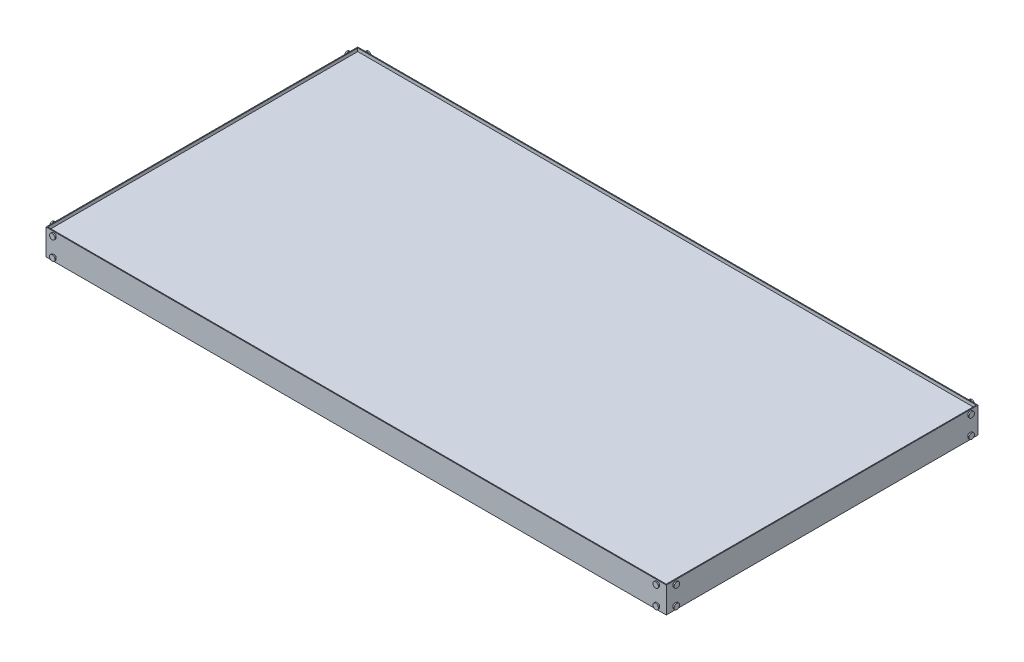
SolidWorks part; units mm, degrees
material "Plain Carbon Steel"
ref_plane "Front Plane" through (0, 0, 0) normal (0, 0, 1) x (1, 0, 0)
ref_plane "Top Plane" through (0, 0, 0) normal (0, 1, 0) x (1, 0, 0)
ref_plane "Right Plane" through (0, 0, 0) normal (1, 0, 0) x (0, 0, -1)
sketch "Sketch1" plane through (0, 0, 0) normal (0, 1, 0) x (1, 0, 0)
  line L1 (-612.775, -307.975) -> (612.775, -307.975)
  line L2 (-612.775, -307.975) -> (-612.775, 307.975)
  line L3 (-612.775, 307.975) -> (612.775, 307.975)
  line L4 (612.775, -307.975) -> (612.775, 307.975)
  line L5 (-612.775, -307.975) -> (612.775, 307.975) construction
  line L6 (-612.775, 307.975) -> (612.775, -307.975) construction
  point P0 (0, 0)
  dimension "D1" = 1225.55
  dimension "D2" = 615.95
ref_plane "Plane1" through (0, 5.08, 0) normal (0, 1, 0) x (1, 0, 0)
sketch "Sketch2" plane through (0, 5.08, 0) normal (0, 1, 0) x (1, 0, 0)
  line L0 (612.775, -307.975) -> (612.775, 307.975) construction
  line L1 (-612.775, 307.975) -> (612.775, 307.975)
  line L2 (-612.775, 307.975) -> (-612.775, -307.975)
  line L3 (-612.775, -307.975) -> (612.775, -307.975)
  line L4 (612.775, 307.975) -> (612.775, -307.975)
  line L5 (-612.775, 307.975) -> (612.775, 307.975) construction
  line L6 (-612.775, -307.975) -> (-612.775, 307.975) construction
  line L7 (-612.775, -307.975) -> (612.775, -307.975) construction
extrude "Boss-Extrude1" add sketch "Sketch2" against normal blind 51.308
sketch "Sketch3" plane through (0, 5.08, 0) normal (0, 1, 0) x (1, 0, 0)
  line L8 (-611.124, 306.324) -> (-611.124, -306.324)
  line L9 (-611.124, -306.324) -> (611.124, -306.324)
  line L10 (611.124, -306.324) -> (611.124, 306.324)
  line L11 (611.124, 306.324) -> (-611.124, 306.324)
  line L12 (-611.124, 306.324) -> (-611.124, -306.324)
  line L13 (-611.124, -306.324) -> (611.124, -306.324)
  line L14 (611.124, -306.324) -> (611.124, 306.324)
  line L15 (611.124, 306.324) -> (-611.124, 306.324)
  dimension "D1" = 1.651
extrude "Cut-Extrude1" cut sketch "Sketch3" against normal blind 13.1064
sketch "Sketch4" plane through (0, -8.0264, 0) normal (0, 1, 0) x (1, 0, 0)
  line L1 (-609.6, -304.8) -> (609.6, -304.8)
  line L2 (-609.6, -304.8) -> (-609.6, 304.8)
  line L3 (-609.6, 304.8) -> (609.6, 304.8)
  line L4 (609.6, -304.8) -> (609.6, 304.8)
  line L5 (-609.6, -304.8) -> (609.6, 304.8) construction
  line L6 (-609.6, 304.8) -> (609.6, -304.8) construction
  point P0 (0, 0)
  dimension "D1" = 1219.2
  dimension "D2" = 609.6
extrude "Boss-Extrude2" add sketch "Sketch4" along normal offset from surface (8.3312 mm away) 4.7752 separate body up to face at (0, 5.08, 0)
sketch "Sketch5" plane through (0, 0, 307.975) normal (0, 0, 1) x (1, 0, 0)
  line L0 (612.775, -46.228) -> (612.775, 5.08) construction
  line L1 (-612.775, 5.08) -> (612.775, 5.08) construction
  line L2 (596.0872, -0.9652) -> (596.0872, -37.5412) construction
  circle A0 centre (596.0872, -0.9652) radius 5.461 construction
  circle A1 centre (596.0872, -0.9652) radius 3.556
  circle A2 centre (596.0872, -37.5412) radius 3.556
  dimension "D2" = 10.922
  dimension "D4" = 7.112
  dimension "D1" = 11.2268
  dimension "D3" = 11.5062
  dimension "D5" = 36.576
extrude "Boss-Extrude3" add sketch "Sketch5" along normal blind 2.032
sketch "Sketch6" plane through (0, 0, 310.007) normal (0, 0, 1) x (1, 0, 0)
  circle A0 centre (596.0872, -0.9652) radius 5.461
  circle A1 centre (596.0872, -37.5412) radius 5.461
  circle A2 centre (596.0872, -37.5412) radius 3.556 construction
  circle A3 centre (596.0872, -0.9652) radius 3.556 construction
  circle A4 centre (596.0872, -0.9652) radius 5.461 construction
extrude "Boss-Extrude4" add sketch "Sketch6" along normal offset from surface (2.286 mm away) 4.318 up to face at (599.6432, -37.5412, 307.975) offset beyond the face yes
sketch "Sketch7" plane through (612.775, 0, 0) normal (1, 0, 0) x (0, 0, -1)
  line L0 (-291.2872, -0.9652) -> (-291.2872, -37.5412) construction
  line L1 (-307.975, -46.228) -> (-307.975, 5.08) construction
  line L2 (-307.975, 5.08) -> (307.975, 5.08) construction
  circle A0 centre (-291.2872, -0.9652) radius 5.461 construction
  circle A1 centre (-291.2872, -0.9652) radius 3.556
  circle A2 centre (-291.2872, -37.5412) radius 3.556
  dimension "D2" = 10.922
  dimension "D4" = 7.112
  dimension "D1" = 11.2268
  dimension "D3" = 11.5062
  dimension "D5" = 36.576
extrude "Boss-Extrude5" add sketch "Sketch7" along normal blind 2.032
sketch "Sketch8" plane through (614.807, 0, 0) normal (1, 0, 0) x (0, 0, -1)
  circle A0 centre (-291.2872, -0.9652) radius 5.461
  circle A1 centre (-291.2872, -37.5412) radius 5.461
  circle A2 centre (-291.2872, -37.5412) radius 3.556 construction
  circle A4 centre (-291.2872, -0.9652) radius 5.461 construction
extrude "Boss-Extrude6" add sketch "Sketch8" along normal offset from surface (2.286 mm away) 4.318 up to face at (612.775, -37.5412, 287.7312) offset beyond the face yes
mirror "Mirror2" about plane through (0, 0, 0) normal (0, 0, 1) of "Boss-Extrude6", "Boss-Extrude5", "Boss-Extrude4", "Boss-Extrude3"
mirror "Mirror3" about plane through (0, 0, 0) normal (1, 0, 0) of "Mirror2", "Boss-Extrude6", "Boss-Extrude5", "Boss-Extrude4", "Boss-Extrude3"
equation "\"D1@Sketch7\"=\"D1@Sketch5\""
equation "\"D2@Sketch7\"=\"D2@Sketch5\""
equation "\"D3@Sketch7\"=\"D3@Sketch5\""
equation "\"D4@Sketch7\"=\"D4@Sketch5\""
equation "\"D5@Sketch7\"=\"D5@Sketch5\""
equation "\"D1@Boss-Extrude5\"= \"D1@Boss-Extrude3\""
equation "\"D1@Boss-Extrude6\"= \"D1@Boss-Extrude4\""
